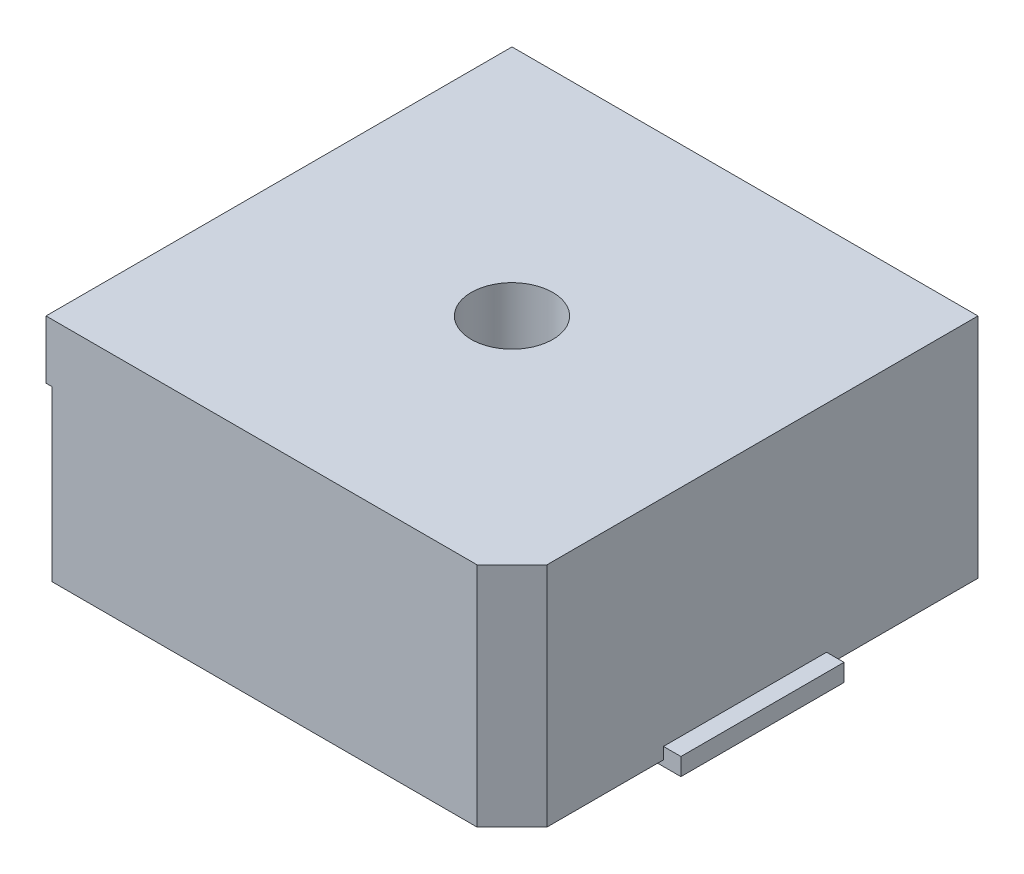
SolidWorks part; units mm, degrees
ref_plane "Front Plane" through (0, 0, 0) normal (0, 0, 1) x (1, 0, 0)
ref_plane "Top Plane" through (0, 0, 0) normal (0, 1, 0) x (1, 0, 0)
ref_plane "Right Plane" through (0, 0, 0) normal (1, 0, 0) x (0, 0, -1)
sketch "Sketch1" plane through (0, 0, 0) normal (0, 1, 0) x (1, 0, 0)
  line L1 (2, 2) -> (-2, 2)
  line L2 (2, 2) -> (2, -2)
  line L3 (2, -2) -> (-2, -2)
  line L4 (-2, 2) -> (-2, -2)
  line L5 (2, 2) -> (-2, -2) construction
  line L6 (2, -2) -> (-2, 2) construction
  point P0 (0, 0)
  dimension "D1" = 4
extrude "Boss-Extrude1" add sketch "Sketch1" along normal blind 2
sketch "Sketch2" plane through (0, 2, 0) normal (0, 1, 0) x (1, 0, 0)
  line L0 (2, -1.7) -> (1.7, -2)
  line L1 (2, -2) -> (2, 2) construction
  line L2 (-2, -2) -> (2, -2) construction
  line L3 (1.7, -2) -> (2, -2)
  line L4 (2, -2) -> (2, -1.7)
  dimension "D1" = 45
  dimension "D2" = 0.3
extrude "Cut-Extrude1" cut sketch "Sketch2" against normal up to surface (2 mm away) up to face at (0, 0, 0)
sketch "Sketch3" plane through (0, 0, 0) normal (-1, 0, 0) x (0, 0, 1)
  line L0 (-0.7, 0) -> (-0.7, 0.15)
  line L1 (-2, 0) -> (2, 0) construction
  line L2 (-0.7, 0.15) -> (0.7, 0.15)
  line L3 (0.7, 0.15) -> (0.7, 0)
  line L4 (0.7, 0) -> (-0.7, 0)
  point P4 (0, 0.15)
  dimension "D1" = 0.15
  dimension "D2" = 1.4
extrude "Boss-Extrude2" add sketch "Sketch3" along normal mid plane 4.3
sketch "Sketch5" plane through (0, 0, 0) normal (0, -1, 0) x (-1, 0, 0)
  circle A0 centre (0, 0) radius 0.35
  dimension "D1" = 0.7
extrude "Cut-Extrude4" cut sketch "Sketch5" against normal up to surface (2 mm away) up to face at (0.34, 2, 0.34)
sketch "Sketch6" plane through (0, 0, 0) normal (0, -1, 0) x (1, 0, 0)
  line L0 (-2.15, 0.7) -> (-1.65, 0.7)
  line L1 (-1.65, 0.7) -> (-1.65, -0.7)
  line L2 (-1.65, -0.7) -> (-2.15, -0.7)
  line L3 (-2.15, -0.7) -> (-2.15, 0.7)
  line L4 (2.15, 0.7) -> (1.65, 0.7)
  line L5 (1.65, 0.7) -> (1.65, -0.7)
  line L6 (1.65, -0.7) -> (2.15, -0.7)
  line L7 (2.15, -0.7) -> (2.15, 0.7)
  dimension "D1" = 0.5
sketch "Sketch7" plane through (0, 0, 0) normal (0, -1, 0) x (1, 0, 0)
  line L4 (2.15, 0.7) -> (1.65, 0.7)
  line L5 (1.65, 0.7) -> (1.65, -0.7)
  line L6 (1.65, -0.7) -> (2.15, -0.7)
  line L7 (2.15, -0.7) -> (2.15, 0.7)
  line L8 (2, 0.7) -> (1.65, 0.7)
  line L9 (1.65, 0.7) -> (1.65, -0.7)
  line L10 (1.65, -0.7) -> (2, -0.7)
  line L12 (-1.65, 0.7) -> (-2.15, 0.7)
  line L13 (2, -2) -> (2, -0.7)
  line L14 (2, -0.7) -> (2.15, -0.7)
  line L15 (2.15, -0.7) -> (2.15, 0.7)
  line L16 (2.15, 0.7) -> (2, 0.7)
  line L17 (2, 0.7) -> (2, 1.7)
  line L18 (2, 1.7) -> (1.7, 2)
  line L19 (1.7, 2) -> (-2, 2)
  line L20 (-2, 2) -> (-2, 0.7)
  line L21 (-2, 0.7) -> (-2.15, 0.7)
  line L22 (-2.15, 0.7) -> (-2.15, -0.7)
  line L23 (-2.15, -0.7) -> (-2, -0.7)
  line L24 (-2, -0.7) -> (-2, -2)
  line L25 (-2, -2) -> (2, -2)
  line L26 (2, -2) -> (2, -0.7)
  line L30 (2, 0.7) -> (2, 1.7)
  line L31 (2, 1.7) -> (1.7, 2)
  line L32 (1.7, 2) -> (-2, 2)
  line L33 (-2, 2) -> (-2, 0.7)
  line L37 (-2, -0.7) -> (-2, -2)
  line L38 (-2, -2) -> (2, -2)
  line L39 (-1.65, -0.7) -> (-1.65, 0.7)
  line L40 (-2.15, -0.7) -> (-1.65, -0.7)
  line L41 (-2.15, 0.7) -> (-2.15, -0.7)
  line L42 (-1.65, 0.7) -> (-2, 0.7)
  line L43 (-1.65, -0.7) -> (-1.65, 0.7)
  line L44 (-2, -0.7) -> (-1.65, -0.7)
  dimension "D1" = 0
  dimension "D2" = 0
  dimension "D3" = 0
extrude "Cut-Extrude5" cut sketch "Sketch7" against normal blind 0.05
sketch "Sketch8" plane through (0, 0.05, 0) normal (0, -1, 0) x (1, 0, 0)
  line L0 (1, 0) -> (-1, 0) construction
  circle A0 centre (-1, 0) radius 0.1
  circle A1 centre (1, 0) radius 0.1
  point P4 (0, 0)
  dimension "D2" = 0.2
  dimension "D1" = 2
extrude "Cut-Extrude6" cut sketch "Sketch8" against normal blind 1.5
sketch "Sketch9" plane through (-2, 0, 0) normal (-1, 0, 0) x (0, 0, 1)
  line L0 (-2, 1.5) -> (-1.875, 1.5)
  line L1 (-2, 2) -> (-2, 0.05) construction
  line L2 (-1.875, 1.5) -> (-1.875, 1.9)
  line L3 (0, 0) -> (0, 1.9) construction
  line L4 (1.875, 1.9) -> (-1.875, 1.9)
  line L5 (-2, 2) -> (2, 2) construction
  line L6 (1.875, 1.9) -> (1.875, 1.5)
  line L7 (1.875, 1.5) -> (2, 1.5)
  line L8 (2, 2) -> (2, 0.05) construction
  line L9 (-0.75, 0.05) -> (-0.75, 1.7)
  line L10 (-0.7, 0.05) -> (-2, 0.05) construction
  line L11 (-0.75, 1.7) -> (0.75, 1.7)
  line L12 (0.75, 1.7) -> (0.75, 0.05)
  line L13 (2, 0.05) -> (0.7, 0.05) construction
  line L14 (0.75, 0.05) -> (2, 0.05)
  line L15 (2, 0.05) -> (2, 1.5)
  line L16 (-2, 1.5) -> (-2, 0.05)
  line L17 (-2, 0.05) -> (-0.75, 0.05)
  point P10 (0, 1.9)
  point P21 (0, 1.7)
  dimension "D1" = 0.1
  dimension "D2" = 3.75
  dimension "D3" = 0.5
  dimension "D4" = 0.2
  dimension "D5" = 1.5
extrude "Cut-Extrude7" cut sketch "Sketch9" against normal blind 0.05
